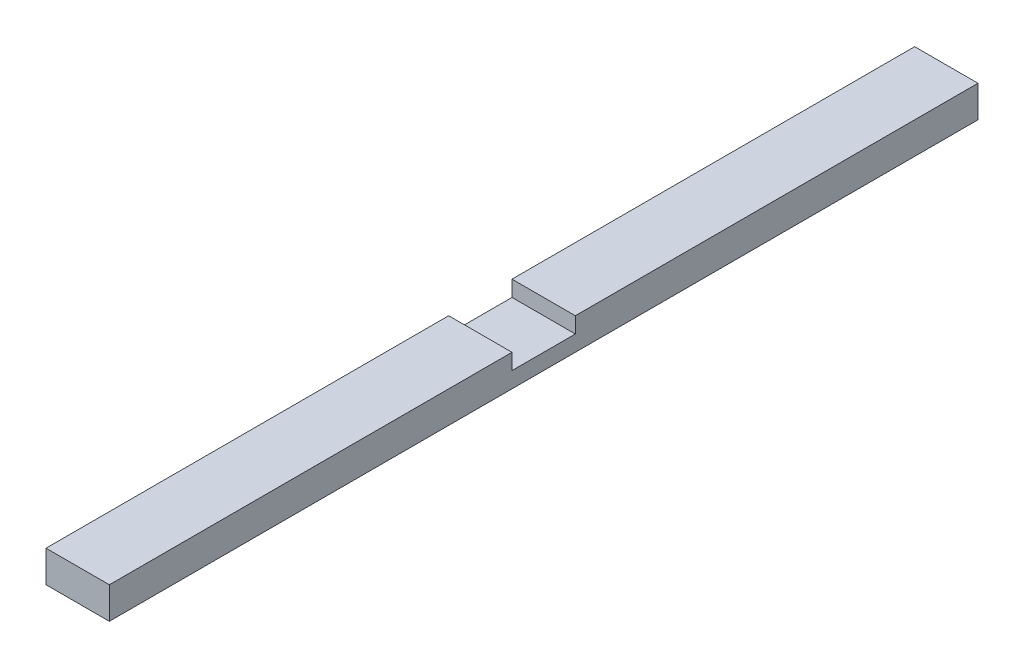
SolidWorks part; units mm, degrees
ref_plane "Front Plane" through (0, 0, 0) normal (0, 0, 1) x (1, 0, 0)
ref_plane "Top Plane" through (0, 0, 0) normal (0, 1, 0) x (1, 0, 0)
ref_plane "Right Plane" through (0, 0, 0) normal (1, 0, 0) x (0, 0, -1)
sketch "Sketch1" plane through (0, 0, 0) normal (0, 0, 1) x (1, 0, 0)
  line L1 (-44.45, -22.225) -> (44.45, -22.225)
  line L2 (-44.45, -22.225) -> (-44.45, 22.225)
  line L3 (-44.45, 22.225) -> (44.45, 22.225)
  line L4 (44.45, -22.225) -> (44.45, 22.225)
  line L5 (-44.45, -22.225) -> (44.45, 22.225) construction
  line L6 (-44.45, 22.225) -> (44.45, -22.225) construction
  point P0 (0, 0)
  dimension "D1" = 44.45
  dimension "D2" = 88.9
extrude "Boss-Extrude1" add sketch "Sketch1" along normal blind 1219.2
sketch "Sketch2" plane through (0, 22.225, 0) normal (0, 1, 0) x (1, 0, 0)
  line L0 (0, 0) -> (0, -1219.2) construction
  line L1 (44.45, -1219.2) -> (-44.45, -1219.2) construction
  line L2 (-44.45, -609.6) -> (44.45, -609.6) construction
  line L3 (-44.45, -1219.2) -> (-44.45, 0) construction
  line L4 (44.45, -1219.2) -> (44.45, 0) construction
  line L6 (-44.45, -654.05) -> (44.45, -654.05)
  line L7 (-44.45, -654.05) -> (-44.45, -565.15)
  line L8 (-44.45, -565.15) -> (44.45, -565.15)
  line L9 (44.45, -654.05) -> (44.45, -565.15)
  line L10 (-44.45, -654.05) -> (44.45, -565.15) construction
  line L11 (-44.45, -565.15) -> (44.45, -654.05) construction
  point P3 (0, -609.6)
  dimension "D1" = 88.9
extrude "Cut-Extrude1" cut sketch "Sketch2" against normal blind 22.225
